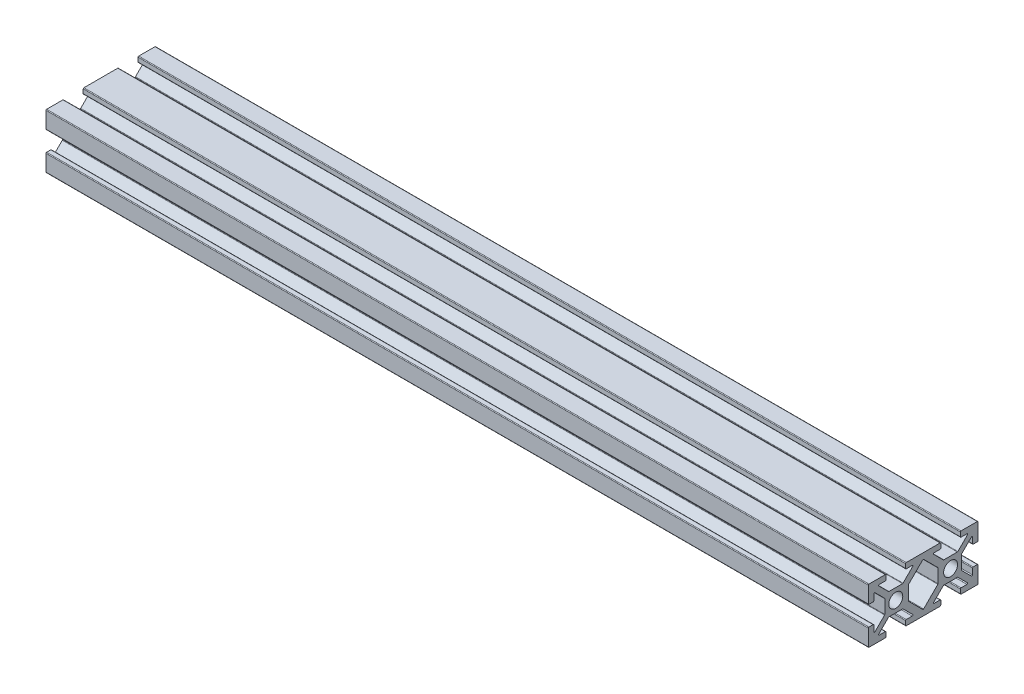
SolidWorks part; units mm, degrees
ref_plane "Front Plane" through (0, 0, 0) normal (0, 0, 1) x (1, 0, 0)
ref_plane "Top Plane" through (0, 0, 0) normal (0, 1, 0) x (1, 0, 0)
ref_plane "Right Plane" through (0, 0, 0) normal (1, 0, 0) x (0, 0, -1)
sketch "Sketch2" plane through (0, 0, 0) normal (1, 0, 0) x (0, 0, -1)
  line L0 (-20, 13.5858) -> (-20, 20)
  line L1 (-20, 20) -> (-13.5858, 20)
  line L2 (-13.5858, 20) -> (-13.5858, 18)
  line L3 (-13.5858, 18) -> (-16.5858, 18)
  line L4 (-16.5858, 18) -> (-12.5858, 14)
  line L5 (-12.5858, 14) -> (-7.4142, 14)
  line L6 (-7.4142, 14) -> (-3.4142, 18)
  line L7 (-3.4142, 18) -> (-6.4142, 18)
  line L8 (-6.4142, 18) -> (-6.4142, 20)
  line L9 (-6.4142, 20) -> (0, 20)
  line L10 (0, 20) -> (0, 18)
  line L11 (0, 18) -> (-5.4142, 12.5858)
  line L12 (-5.4142, 12.5858) -> (-5.4142, 7.4142)
  line L13 (-5.4142, 7.4142) -> (0, 2)
  line L14 (0, 2) -> (0, 0)
  line L15 (0, 0) -> (-6.4142, 0)
  line L16 (-6.4142, 0) -> (-6.4142, 2)
  line L17 (-6.4142, 2) -> (-3.4142, 2)
  line L18 (-3.4142, 2) -> (-7.4142, 6)
  line L19 (-7.4142, 6) -> (-12.5858, 6)
  line L20 (-12.5858, 6) -> (-16.5858, 2)
  line L21 (-16.5858, 2) -> (-13.5858, 2)
  line L22 (-13.5858, 2) -> (-13.5858, 0)
  line L23 (-13.5858, 0) -> (-20, 0)
  line L24 (-20, 0) -> (-20, 6.4142)
  line L25 (-20, 6.4142) -> (-18, 6.4142)
  line L26 (-18, 6.4142) -> (-18, 3.4142)
  line L27 (-18, 3.4142) -> (-14, 7.4142)
  line L28 (-14, 7.4142) -> (-14, 12.5858)
  line L29 (-14, 12.5858) -> (-18, 16.5858)
  line L30 (-18, 16.5858) -> (-18, 13.5858)
  line L31 (-18, 13.5858) -> (-20, 13.5858)
  line L32 (-10, 14) -> (-10, 6) construction
  line L33 (-14, 10) -> (-5.4142, 10) construction
  line L34 (0, 55) -> (0, -55) construction
  line L35 (22, 0) -> (-22, 0) construction
  circle A0 centre (-10, 10) radius 2.55
  point P37 (-5.4142, 10)
  point P38 (-14, 10)
  dimension "D9" = 5.1
  dimension "D1" = 20
  dimension "D2" = 2
  dimension "D3" = 3
  dimension "D4" = 2
  dimension "D5" = 20
  dimension "D6" = 20
  dimension "D7" = 2
  dimension "D8" = 8
  dimension "D10" = 0
extrude "Boss-Extrude2" add sketch "Sketch2" along normal blind 300
fillet "Fillet1" radius 0.25 28 edges at (150, 18, 16.5858) (150, 16.5858, 18) (150, 18, 3.4142) (150, 20, 6.4142) (150, 18, 6.4142) (150, 14, 7.4142) (150, 0, 6.4142) (150, 2, 6.4142) (150, 7.4142, 5.4142) (150, 2, 3.4142) (150, 6, 7.4142) (150, 6, 12.5858) (150, 0, 13.5858) (150, 2, 13.5858) (150, 2, 16.5858) (150, 7.4142, 14) (150, 18, 13.5858) (150, 20, 13.5858) (150, 20, 20) (150, 13.5858, 18) (150, 13.5858, 20) (150, 6.4142, 20) (150, 6.4142, 18) (150, 0, 20) (150, 3.4142, 18) (150, 12.5858, 14) (150, 14, 12.5858) (150, 12.5858, 5.4142)
mirror "Mirror3" about plane through (300, 20, 0) normal (0, 0, 1) of bodies 107
fillet "Fillet2" radius 0.25 2 edges at (150, 2, 0) (150, 18, 0)
ref_plane "Plane1" through (0, 10, 0) normal (0, 1, 0) x (1, 0, 0)
